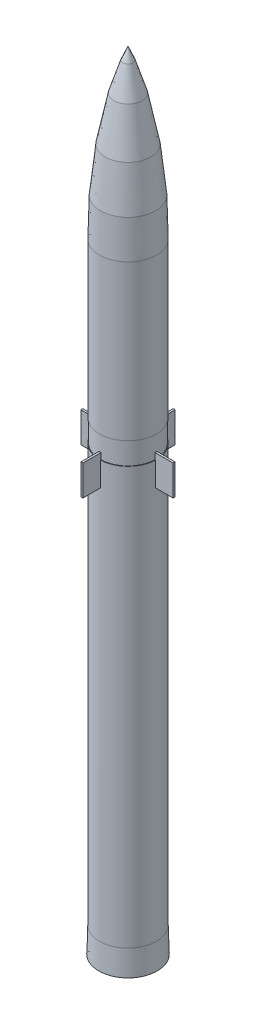
SolidWorks part; units mm, degrees
ref_plane "Front Plane" through (0, 0, 0) normal (0, 0, 1) x (1, 0, 0)
ref_plane "Top Plane" through (0, 0, 0) normal (0, 1, 0) x (1, 0, 0)
ref_plane "Right Plane" through (0, 0, 0) normal (1, 0, 0) x (0, 0, -1)
sketch "Sketch1" plane through (0, 0, 0) normal (0, 0, 1) x (1, 0, 0)
  line L0 (0, 0) -> (0, 124400) construction
  line L1 (0, 124400) -> (800, 122500)
  line L2 (800, 122500) -> (2200, 118000)
  line L3 (2200, 118000) -> (3600, 111000)
  line L4 (3600, 111000) -> (4350, 104000)
  line L5 (4350, 104000) -> (4500, 98000)
  line L6 (4500, 98000) -> (4500, 73500)
  line L7 (4500, 73500) -> (4420, 73500)
  line L8 (4420, 73500) -> (4420, 70000)
  line L9 (4420, 70000) -> (4500, 70000)
  line L10 (4500, 70000) -> (4500, 4000)
  line L11 (4500, 4000) -> (4620, 0)
  line L12 (4620, 0) -> (4300, 0)
  line L13 (4300, 0) -> (4300, 1500)
  line L14 (4300, 1500) -> (0, 4000)
  line L15 (0, 4000) -> (0, 124400)
revolve "Revolve1" add sketch "Sketch1" angle 360 about L0
sketch "Sketch2" plane through (0, 0, 0) normal (0, 0, 1) x (1, 0, 0)
  line L0 (0, 0) -> (0, 4000) construction
  line L1 (4500, 4000) -> (-4500, 4000) construction
  line L2 (0, 4000) -> (0, 0)
  line L3 (0, 0) -> (580, -650)
  line L4 (580, -650) -> (0, 4000)
  line L5 (0, 4000) -> (0, 3200)
  line L6 (0, 3200) -> (580, -650)
  line L7 (580, -650) -> (2350, -650)
  line L8 (2350, -650) -> (0, 3200)
  line L9 (0, 3200) -> (1550, 2700)
  line L10 (1550, 2700) -> (2350, -650)
  line L11 (2350, -650) -> (4180, -650)
  line L12 (4180, -650) -> (1550, 2700)
  line L13 (1550, 2700) -> (3200, 2500)
sketch "Sketch3" plane through (0, 0, 0) normal (0, 0, 1) x (1, 0, 0)
  line L0 (0, 68000) -> (0, 78000) construction
  line L1 (0, 73000) -> (0, 71000)
  line L2 (0, 71000) -> (580, 71000)
  line L3 (580, 71000) -> (0, 73000)
  line L4 (580, 73000) -> (3800, 71000)
  line L5 (3800, 71000) -> (3700, 70800)
  line L6 (3700, 70800) -> (580, 73000)
  line L7 (580, 73000) -> (2200, 75000)
sketch "Sketch4" plane through (0, 0, 0) normal (0, 0, 1) x (1, 0, 0)
  line L0 (3800, 71000) -> (7300, 71000)
  line L1 (7300, 71000) -> (7300, 66200)
  line L2 (7300, 66200) -> (3800, 66200)
  line L3 (3800, 66200) -> (3800, 71000)
extrude "Boss-Extrude1" add sketch "Sketch4" along normal mid plane 320
pattern_circular "CirPattern1" count 4 over 360 about axis through (0, 0, 0) along (0, 1, 0) of "Boss-Extrude1"
sketch "Sketch5" plane through (0, 0, 0) normal (0, 0, 1) x (1, 0, 0)
  line L0 (3500, 85500) -> (8550, 80450)
  line L1 (8550, 80450) -> (8550, 74500)
  line L2 (8550, 74500) -> (2200, 75000)
  line L3 (2200, 75000) -> (3500, 85500)
  line L4 (3500, 85500) -> (3500, 80450)
  line L5 (3500, 80450) -> (2200, 75000)
  line L6 (2200, 75000) -> (3500, 85500)
  line L7 (-3500, 85500) -> (-7600, 80250)
  line L8 (-7600, 80250) -> (-7600, 75000)
  line L9 (-7600, 75000) -> (-3500, 73500)
  line L10 (-4500, 73500) -> (4500, 73500) construction
  line L11 (-3500, 73500) -> (-3500, 85500)
  line L12 (-3500, 85500) -> (-3500, 79500)
  line L13 (-3500, 79500) -> (-3500, 73500)
  line L14 (-3500, 73500) -> (-3500, 85500)
sketch "Sketch6" plane through (0, 0, 0) normal (1, 0, 0) x (0, 0, -1)
  line L0 (4497.1547, 70000) -> (4497.1547, 0)
  line L1 (4497.1547, 0) -> (4400, 2000)
  line L2 (4400, 2000) -> (4497.1547, 70000)
  line L3 (4497.1547, 105000) -> (4500, 75000)
  line L4 (4500, 73500) -> (4500, 98000) construction
  line L5 (4500, 75000) -> (4400, 75000)
  line L6 (4400, 75000) -> (4497.1547, 105000)
extrude "Boss-Extrude4" add sketch "Sketch6" along normal mid plane 220
sketch "Sketch7" plane through (0, 0, 0) normal (0, 0, 1) x (1, 0, 0)
  line L0 (0, 73000) -> (0, 124400) construction
  line L1 (0, 124400) -> (820, 122520)
  line L2 (820, 122520) -> (820, 118020)
  line L3 (820, 118020) -> (3600, 111000)
  line L4 (3600, 111000) -> (3600, 104020)
  line L5 (3600, 104020) -> (3600, 98000)
  line L6 (3600, 98000) -> (4500, 73500)
  line L7 (4500, 73500) -> (3600, 98000)
  line L8 (3600, 98000) -> (3600, 104020)
  line L9 (3600, 104020) -> (3600, 111000)
  line L10 (3600, 111000) -> (820, 118020)
  line L11 (820, 118020) -> (820, 122520)
  line L12 (820, 122520) -> (0, 124400)
  line L13 (0, 124400) -> (0, 124420)
